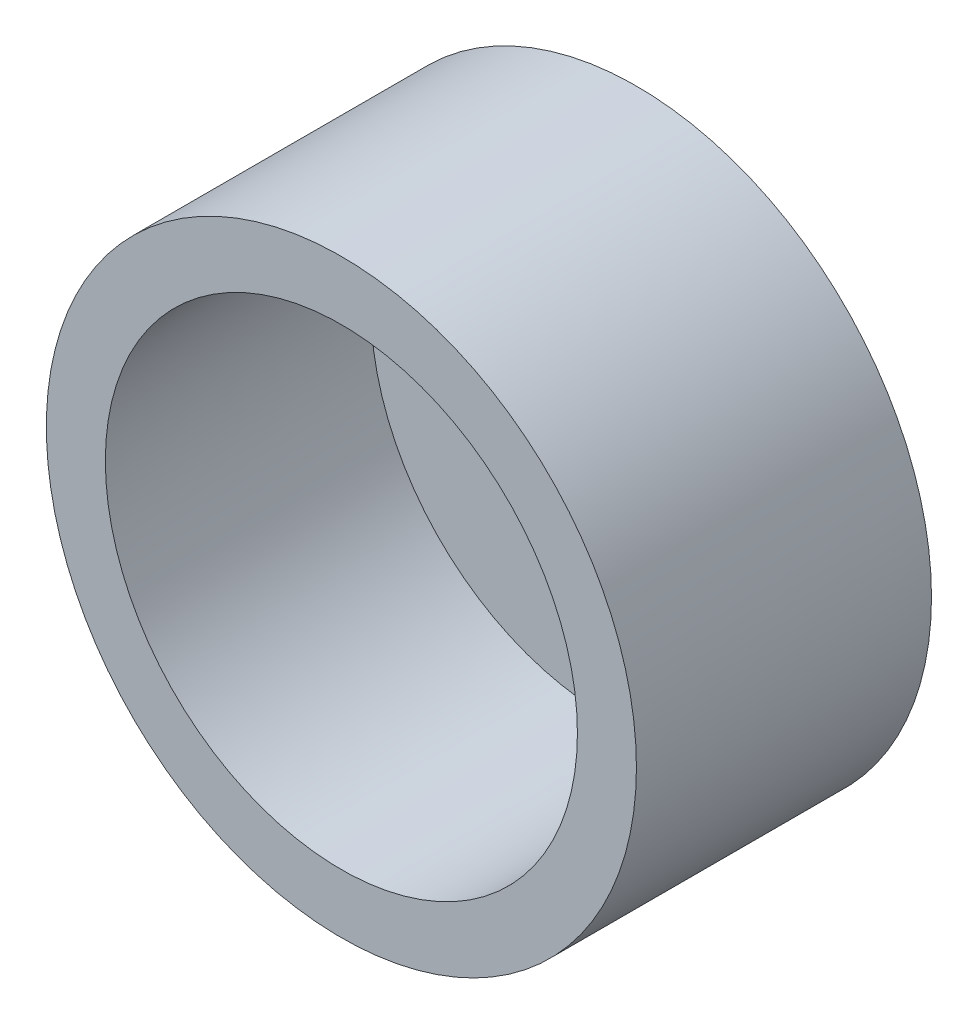
SolidWorks part; units mm, degrees
ref_plane "Front Plane" through (0, 0, 0) normal (0, 0, 1) x (1, 0, 0)
ref_plane "Top Plane" through (0, 0, 0) normal (0, 1, 0) x (1, 0, 0)
ref_plane "Right Plane" through (0, 0, 0) normal (1, 0, 0) x (0, 0, -1)
sketch "Sketch1" plane through (0, 0, 0) normal (0, 0, 1) x (1, 0, 0)
  circle A0 centre (0, 0) radius 5
  circle A1 centre (0, 0) radius 4
extrude "Boss-Extrude1" add sketch "Sketch1" along normal blind 5 contours A0
sketch "Sketch3" plane through (0, 0, 5) normal (0, 0, 1) x (1, 0, 0)
  circle A0 centre (0, 0) radius 4
extrude "Cut-Extrude1" cut sketch "Sketch3" against normal blind 4.5
sketch "Sketch4" plane through (0, 0, 0.5) normal (0, 0, 1) x (1, 0, 0)
  line L0 (0, 0) -> (4, 0) construction
  line L1 (4, 0) -> (-4, 0) construction
  line L2 (0, 4) -> (0, -4) construction
  circle A0 centre (0, 0) radius 4 construction
  circle A1 centre (0, 0) radius 4 construction
  circle A2 centre (1.29, 0) radius 0.3
  circle A3 centre (-1.29, 0) radius 0.3
  dimension "D1" = 1.29
  dimension "D2" = 1.29
extrude "Cut-Extrude2" cut sketch "Sketch4" against normal through all
